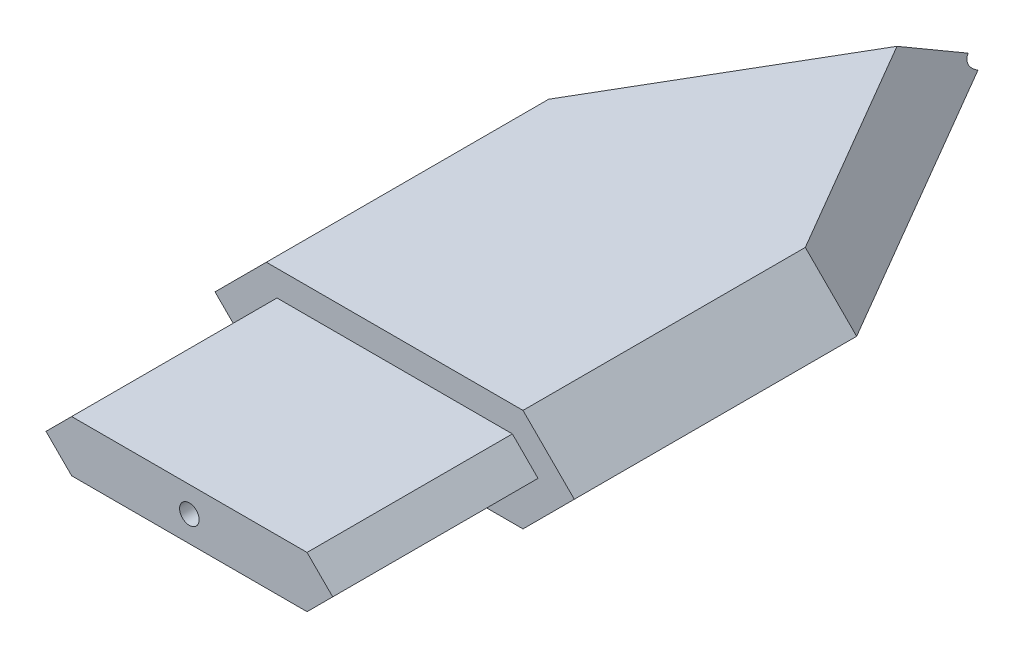
SolidWorks part; units mm, degrees
ref_plane "前视基准面" through (0, 0, 0) normal (0, 0, 1) x (1, 0, 0)
ref_plane "上视基准面" through (0, 0, 0) normal (0, 1, 0) x (1, 0, 0)
ref_plane "右视基准面" through (0, 0, 0) normal (1, 0, 0) x (0, 0, -1)
sketch "草图1" plane through (0, 0, 0) normal (0, 1, 0) x (1, 0, 0)
  line L0 (0, 0) -> (0, 690) construction
  line L1 (0, 690) -> (0, 630) construction
  line L2 (-35, 0) -> (35, 0)
  line L3 (-35, 0) -> (-35, 630)
  line L4 (-35, 630) -> (0, 690)
  line L5 (35, 630) -> (0, 690)
  line L6 (35, 0) -> (35, 630)
  dimension "D1" = 690
  dimension "D2" = 60
  dimension "D3" = 70
ref_plane "基准面1" through (0, 10, 0) normal (0, 1, 0) x (1, 0, 0)
sketch "草图4" plane through (0, 10, 0) normal (0, 1, 0) x (1, 0, 0)
  line L0 (25, 0) -> (-25, 0)
  line L1 (-25, 0) -> (-25, 630)
  line L2 (-25, 630) -> (0, 672.8571)
  line L3 (0, 0) -> (0, 690) construction
  line L4 (-35, 630) -> (0, 690) construction
  line L5 (0, -5.5) -> (0, 5.5) construction
  line L6 (25, 630) -> (0, 672.8571)
  line L7 (25, 0) -> (25, 630)
  point P2 (0, 0)
  dimension "D1" = 50
loft "放样1" add profiles "草图4", "草图1"
mirror "镜向1" about plane through (0, 0, 0) normal (0, 1, 0) of "放样1"
sketch "草图5" plane through (0, 0, 0) normal (0, 1, 0) x (1, 0, 0)
  line L0 (0, -30.5) -> (0, -55.5) construction
  line L1 (0, -55.5) -> (0, -30.5) construction
  line L2 (-79, -30.5) -> (79, -30.5) construction
  line L3 (0, -30.5) -> (0, 0) construction
  arc A0 (-66.3468, -65.1892) -> (66.3468, -65.1892) centre (0, -287.5) cw
  arc A1 (76.7912, -2.3877) -> (76.7912, -58.6123) centre (-101, -30.5) cw
  arc A2 (-76.7912, -2.3877) -> (-76.7912, -58.6123) centre (101, -30.5) ccw
  arc A4 (66.3468, -65.1892) -> (76.7912, -58.6123) centre (68.6918, -57.3316) ccw
  arc A5 (-66.3468, -65.1892) -> (-76.7912, -58.6123) centre (-68.6918, -57.3316) cw
  arc A6 (-76.7912, -2.3877) -> (76.7912, -2.3877) centre (0, 224.9955) ccw
  point P10 (0, -55.5)
  point P15 (79, -30.5)
  dimension "D4" = 232
  dimension "D5" = 180
  dimension "D6" = 8.2
  dimension "D7" = 240
  dimension "D1" = 25
  dimension "D2" = 158
  dimension "D3" = 30.5
extrude "凸台-拉伸1" add sketch "草图5" along normal mid plane 36 separate body
chamfer "倒角1" distance 5 angle 45 11 edges at (79, -18, 30.5) (73.0612, -18, 64.2705) (0, -18, 55.5) (-73.0612, -18, 64.2705) (-79, -18, 30.5) (79, 18, 30.5) (73.0612, 18, 64.2705) (0, 18, 55.5) (-73.0612, 18, 64.2705) (-79, 18, 30.5) (0, 18, 15.0045)
chamfer "倒角2" distance 5 angle 45 1 edges at (0, -18, 15.0045)
sketch "草图6" plane through (0, 18, 0) normal (0, 1, 0) x (1, 0, 0)
  arc A12 (67.2218, -55.0237) -> (68.3355, -15.4837) centre (-101, -30.5) ccw
  arc A13 (-68.3355, -15.4837) -> (68.3355, -15.4837) centre (0, 224.9955) ccw
  arc A14 (-68.3355, -15.4837) -> (-67.2218, -55.0237) centre (101, -30.5) ccw
  arc A15 (67.2218, -55.0237) -> (-67.2218, -55.0237) centre (0, -287.5) ccw
  arc A16 (67.2218, -55.0237) -> (68.3355, -15.4837) centre (-101, -30.5) ccw
  arc A17 (-68.3355, -15.4837) -> (68.3355, -15.4837) centre (0, 224.9955) ccw
  arc A18 (-68.3355, -15.4837) -> (-67.2218, -55.0237) centre (101, -30.5) ccw
  arc A19 (67.2218, -55.0237) -> (-67.2218, -55.0237) centre (0, -287.5) ccw
  dimension "D1" = 5
extrude "切除-拉伸1" cut sketch "草图6" against normal blind 8
mirror "镜向2" about plane through (0, 0, 0) normal (0, 1, 0) of "切除-拉伸1"
sketch "草图7" plane through (0, 0, 0) normal (0, 0, 1) x (1, 0, 0)
  line L12 (-25.8284, 12) -> (-37.8284, 0)
  line L13 (-37.8284, 0) -> (-25.8284, -12)
  line L14 (-25.8284, -12) -> (25.8284, -12)
  line L15 (25.8284, -12) -> (37.8284, 0)
  line L16 (37.8284, 0) -> (25.8284, 12)
  line L17 (25.8284, 12) -> (-25.8284, 12)
  line L18 (-25.8284, 12) -> (-37.8284, 0)
  line L19 (-37.8284, 0) -> (-25.8284, -12)
  line L20 (-25.8284, -12) -> (25.8284, -12)
  line L21 (25.8284, -12) -> (37.8284, 0)
  line L22 (37.8284, 0) -> (25.8284, 12)
  line L23 (25.8284, 12) -> (-25.8284, 12)
  dimension "D1" = 2
extrude "凸台-拉伸2" add sketch "草图7" along normal up to surface (12.0045 mm away)
sketch "草图8" plane through (0, 0, 0) normal (0, 0, -1) x (-1, 0, 0)
  line L6 (25.8284, 12) -> (-25.8284, 12)
  line L7 (-25.8284, 12) -> (-37.8284, 0)
  line L8 (-37.8284, 0) -> (-25.8284, -12)
  line L9 (-25.8284, -12) -> (25.8284, -12)
  line L10 (25.8284, -12) -> (37.8284, 0)
  line L11 (37.8284, 0) -> (25.8284, 12)
  line L12 (25.8284, 12) -> (-25.8284, 12)
  line L13 (-25.8284, 12) -> (-37.8284, 0)
  line L14 (-37.8284, 0) -> (-25.8284, -12)
  line L15 (-25.8284, -12) -> (25.8284, -12)
  line L16 (25.8284, -12) -> (37.8284, 0)
  line L17 (37.8284, 0) -> (25.8284, 12)
  dimension "D1" = 0
extrude "凸台-拉伸3" add sketch "草图8" along normal blind 5
sketch "草图9" plane through (0, 0, 0) normal (0, 1, 0) x (1, 0, 0)
  line L0 (0, 690) -> (0, -310) construction
  line L1 (0, -310) -> (0, -234)
  line L2 (0, -310) -> (0, -256) construction
  line L3 (-22.5, -256) -> (22.5, -256) construction
  line L4 (-22.5, -256) -> (0, -310)
  line L6 (-22.5, -256) -> (-12, -234)
  line L7 (-12, -234) -> (0, -234)
  dimension "D1" = 1000
  dimension "D2" = 76
  dimension "D3" = 54
  dimension "D4" = 45
  dimension "D5" = 12
revolve "旋转1" add sketch "草图9" angle 360 about L0
sketch "草图10" plane through (0, 0, 234) normal (0, 0, -1) x (-1, 0, 0)
  circle A1 centre (0, 0) radius 12
  circle A2 centre (0, 0) radius 12
  dimension "D1" = 0
extrude "凸台-拉伸4" add sketch "草图10" along normal up to next
sketch "草图16" plane through (0, 0, 0) normal (0, 1, 0) x (1, 0, 0)
  line L0 (0, 690) -> (0, -15.0045) construction
  line L1 (35, 630) -> (0, 690) construction
  line L2 (0, 0) -> (0, -20) construction
  line L3 (0, 5) -> (0, -35)
  line L4 (-50, 535) -> (50, 535)
  line L5 (-50, 535) -> (-50, 690)
  line L6 (-50, 690) -> (50, 690)
  line L7 (50, 535) -> (50, 690)
  line L8 (25.8284, 5) -> (-25.8284, 5) construction
  line L9 (0, -35) -> (0, 195)
  line L10 (0, 195) -> (0, 155)
  line L11 (0, 155) -> (0, 385)
  line L12 (0, 385) -> (0, 345)
  line L13 (0, 345) -> (0, 575)
  line L14 (0, 575) -> (0, 535)
  line L15 (0, 535) -> (0, 690)
  arc A0 (-25.8284, -13.6106) -> (25.8284, -13.6106) centre (0, 224.9955) ccw construction
  point P25 (0, 0)
  point P26 (0, 0)
  point P27 (0, 0)
  point P28 (0, 0)
  dimension "D7" = 40
  dimension "D1" = 40
  dimension "D2" = 20
  dimension "D3" = 100
  dimension "D4" = 230
  dimension "D5" = 40
  dimension "D6" = 230
  dimension "D8" = 230
  dimension "D9" = 40
extrude "切除-拉伸7" cut sketch "草图16" against normal through all both and the other way through all flip side to cut
sketch "草图21" plane through (0, 0, -535) normal (0, 0, 1) x (1, 0, 0)
  circle A0 centre (0, 0) radius 1.9
  dimension "D1" = 3.8
extrude "切除-拉伸17" cut sketch "草图21" against normal through all
sketch "草图34" plane through (0, 0, -535) normal (0, 0, 1) x (1, 0, 0)
  line L12 (-22.9289, -5) -> (22.9289, -5)
  line L13 (22.9289, -5) -> (27.9289, 0)
  line L14 (27.9289, 0) -> (22.9289, 5)
  line L15 (22.9289, 5) -> (-22.9289, 5)
  line L16 (-22.9289, 5) -> (-27.9289, 0)
  line L17 (-27.9289, 0) -> (-22.9289, -5)
  line L18 (-22.9289, -5) -> (22.9289, -5)
  line L19 (22.9289, -5) -> (27.9289, 0)
  line L20 (27.9289, 0) -> (22.9289, 5)
  line L21 (22.9289, 5) -> (-22.9289, 5)
  line L22 (-22.9289, 5) -> (-27.9289, 0)
  line L23 (-27.9289, 0) -> (-22.9289, -5)
  dimension "D1" = 5
extrude "切除-拉伸18" cut sketch "草图34" against normal blind 40 flip side to cut
